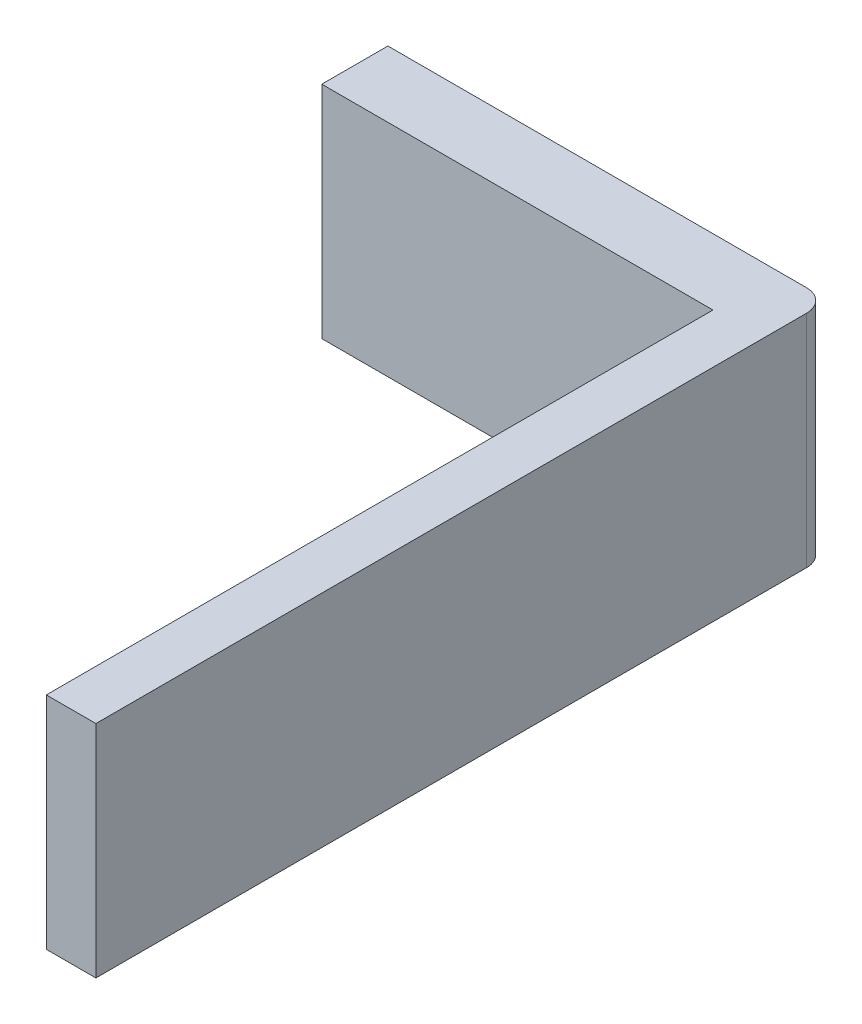
SolidWorks part; units mm, degrees
ref_plane "Front Plane" through (0, 0, 0) normal (0, 0, 1) x (1, 0, 0)
ref_plane "Top Plane" through (0, 0, 0) normal (0, 1, 0) x (1, 0, 0)
ref_plane "Right Plane" through (0, 0, 0) normal (1, 0, 0) x (0, 0, -1)
sketch "Sketch1" plane through (0, 0, 0) normal (0, 1, 0) x (1, 0, 0)
  line L0 (0, 0) -> (-40, 0)
  line L1 (0, 0) -> (0, -65)
extrude "Extrude-Thin1" add sketch "Sketch1" along normal blind 20 thin thin type one direction wall 4.5
sketch "Sketch2" plane through (0, 0, 0) normal (0, 0, -1) x (-1, 0, 0)
  line L1 (0, 20) -> (40, 20)
  line L2 (0, 20) -> (0, 0)
  line L3 (0, 0) -> (40, 0)
  line L4 (40, 20) -> (40, 0)
extrude "Boss-Extrude1" add sketch "Sketch2" along normal blind 1.5
fillet "Fillet1" radius 2 1 edges at (0, 10, -1.5)
